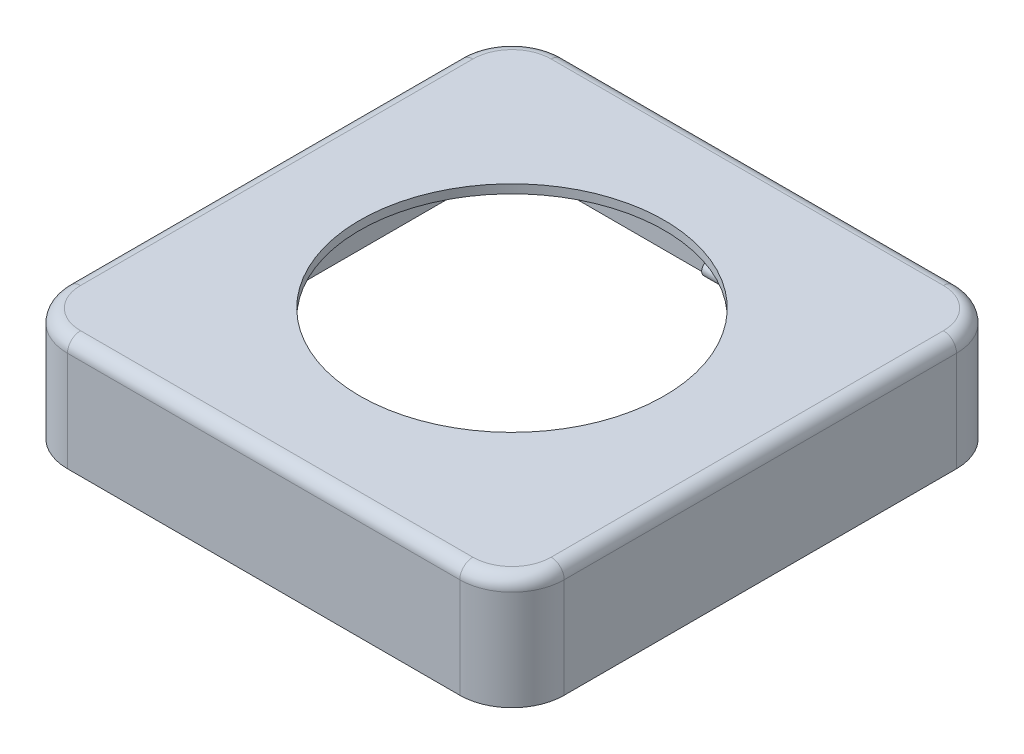
SolidWorks part; units mm, degrees
ref_plane "Front Plane" through (0, 0, 0) normal (0, 0, 1) x (1, 0, 0)
ref_plane "Top Plane" through (0, 0, 0) normal (0, 1, 0) x (1, 0, 0)
ref_plane "Right Plane" through (0, 0, 0) normal (1, 0, 0) x (0, 0, -1)
sketch "Sketch1" plane through (0, 0, 0) normal (0, 1, 0) x (1, 0, 0)
  line L0 (-28.55, 22.55) -> (-28.55, -22.55)
  line L1 (-22.55, 27.55) -> (22.55, 27.55)
  line L2 (-27.55, 22.55) -> (-27.55, -22.55)
  line L3 (-22.55, -27.55) -> (22.55, -27.55)
  line L4 (27.55, 22.55) -> (27.55, -22.55)
  line L5 (-27.55, 27.55) -> (27.55, -27.55) construction
  line L6 (-27.55, -27.55) -> (27.55, 27.55) construction
  line L7 (-22.55, -28.55) -> (22.55, -28.55)
  line L8 (28.55, 22.55) -> (28.55, -22.55)
  line L9 (-22.55, 28.55) -> (22.55, 28.55)
  arc A0 (-27.55, -22.55) -> (-22.55, -27.55) centre (-22.55, -22.55) ccw
  arc A1 (22.55, -27.55) -> (27.55, -22.55) centre (22.55, -22.55) ccw
  arc A2 (22.55, 27.55) -> (27.55, 22.55) centre (22.55, 22.55) cw
  arc A3 (-22.55, 27.55) -> (-27.55, 22.55) centre (-22.55, 22.55) ccw
  arc A4 (-28.55, -22.55) -> (-22.55, -28.55) centre (-22.55, -22.55) ccw
  arc A5 (22.55, -28.55) -> (28.55, -22.55) centre (22.55, -22.55) ccw
  arc A6 (22.55, 28.55) -> (28.55, 22.55) centre (22.55, 22.55) cw
  arc A7 (-22.55, 28.55) -> (-28.55, 22.55) centre (-22.55, 22.55) ccw
  point P0 (0, 0)
  dimension "D3" = 5
  dimension "D1" = 55.1
  dimension "D2" = 55.1
  dimension "D4" = 1
extrude "Boss-Extrude1" add sketch "Sketch1" along normal blind 12
sketch "Sketch2" plane through (0, 12, 0) normal (0, 1, 0) x (1, 0, 0)
  line L0 (-22.55, -28.55) -> (22.55, -28.55) construction
  line L1 (28.55, -22.55) -> (28.55, 22.55) construction
  line L2 (22.55, 28.55) -> (-22.55, 28.55) construction
  line L3 (-28.55, 22.55) -> (-28.55, -22.55) construction
  line L4 (-22.55, -28.55) -> (22.55, -28.55)
  line L5 (28.55, -22.55) -> (28.55, 22.55)
  line L6 (22.55, 28.55) -> (-22.55, 28.55)
  line L7 (-28.55, 22.55) -> (-28.55, -22.55)
  arc A0 (-28.55, -22.55) -> (-22.55, -28.55) centre (-22.55, -22.55) ccw construction
  arc A1 (22.55, -28.55) -> (28.55, -22.55) centre (22.55, -22.55) ccw construction
  arc A2 (28.55, 22.55) -> (22.55, 28.55) centre (22.55, 22.55) ccw construction
  arc A3 (-22.55, 28.55) -> (-28.55, 22.55) centre (-22.55, 22.55) ccw construction
  arc A4 (-28.55, -22.55) -> (-22.55, -28.55) centre (-22.55, -22.55) ccw
  arc A5 (22.55, -28.55) -> (28.55, -22.55) centre (22.55, -22.55) ccw
  arc A6 (28.55, 22.55) -> (22.55, 28.55) centre (22.55, 22.55) ccw
  arc A7 (-22.55, 28.55) -> (-28.55, 22.55) centre (-22.55, 22.55) ccw
  circle A8 centre (0, 0) radius 17.5
  dimension "D1" = 35
extrude "Boss-Extrude2" add sketch "Sketch2" along normal blind 1
ref_plane "Plane1" through (0, 0, 0) normal (-1, 0, 0) x (0, 0, 1)
sketch "Sketch3" plane through (0, 0, 0) normal (-1, 0, 0) x (0, 0, 1)
  line L2 (0, 0) -> (0, 13) construction
  line L3 (-22.55, 0) -> (22.55, 0) construction
  line L4 (-22.55, 13) -> (22.55, 13) construction
  line L5 (-28.55, 0) -> (-22.55, 0) construction
  circle A2 centre (-27.55, 0.75) radius 0.75
  circle A3 centre (27.55, 0.75) radius 0.75
  dimension "D1" = 1.5
  dimension "D2" = 27.55
  dimension "D3" = 0.75
extrude "Boss-Extrude3" add sketch "Sketch3" against normal mid plane 10
fillet "Fillet1" radius 1.5 8 edges at (26.7926, 13, -26.7926) (28.55, 13, 0) (26.7926, 13, 26.7926) (0, 13, 28.55) (-26.7926, 13, 26.7926) (-28.55, 13, 0) (-26.7926, 13, -26.7926) (0, 13, -28.55)
sketch "Sketch4" plane through (-28.55, 0, 0) normal (-1, 0, 0) x (0, 0, 1)
  line L11 (3.19, 3.82) -> (-0.245, 3.82)
  line L12 (4.67, 5.3) -> (4.67, 5.9)
  line L13 (3.19, 7.38) -> (-3.19, 7.38)
  line L14 (-4.67, 5.9) -> (-4.67, 5.3)
  line L15 (-0.255, 3.82) -> (-3.19, 3.82)
  arc A8 (3.19, 3.82) -> (4.67, 5.3) centre (3.19, 5.3) ccw
  arc A9 (4.67, 5.9) -> (3.19, 7.38) centre (3.19, 5.9) ccw
  arc A10 (-3.19, 7.38) -> (-4.67, 5.9) centre (-3.19, 5.9) ccw
  arc A11 (-4.67, 5.3) -> (-3.19, 3.82) centre (-3.19, 5.3) ccw
sketch "Sketch6" plane through (-28.55, 0, 0) normal (-1, 0, 0) x (0, 0, 1)
  line L0 (-3.19, 3.82) -> (3.19, 3.82)
  line L1 (4.67, 5.3) -> (4.67, 5.9)
  line L2 (3.19, 7.38) -> (-3.19, 7.38)
  line L3 (-4.67, 5.9) -> (-4.67, 5.3)
  line L4 (-22.55, 0) -> (22.55, 0) construction
  line L5 (-28.55, 11.5) -> (-28.55, 0) construction
  arc A0 (3.19, 3.82) -> (4.67, 5.3) centre (3.19, 5.3) ccw
  arc A1 (4.67, 5.9) -> (3.19, 7.38) centre (3.19, 5.9) ccw
  arc A2 (-3.19, 7.38) -> (-4.67, 5.9) centre (-3.19, 5.9) ccw
  arc A3 (-4.67, 5.3) -> (-3.19, 3.82) centre (-3.19, 5.3) ccw
  circle A4 centre (-12.78, 7.73) radius 2.85
  dimension "D1" = 5.7
  dimension "D2" = 7.73
  dimension "D3" = 15.77
extrude "Cut-Extrude6" cut sketch "Sketch6" against normal up to next
chamfer "Chamfer1" distance 0.5 angle 45 9 edges at (-28.55, 4.2535, 4.2365) (-28.55, 5.6, 4.67) (-28.55, 3.82, 0) (-28.55, 6.9465, 4.2365) (-28.55, 4.2535, -4.2365) (-28.55, 7.38, 0) (-28.55, 5.6, -4.67) (-28.55, 6.9465, -4.2365) (-28.55, 7.73, -9.93)
